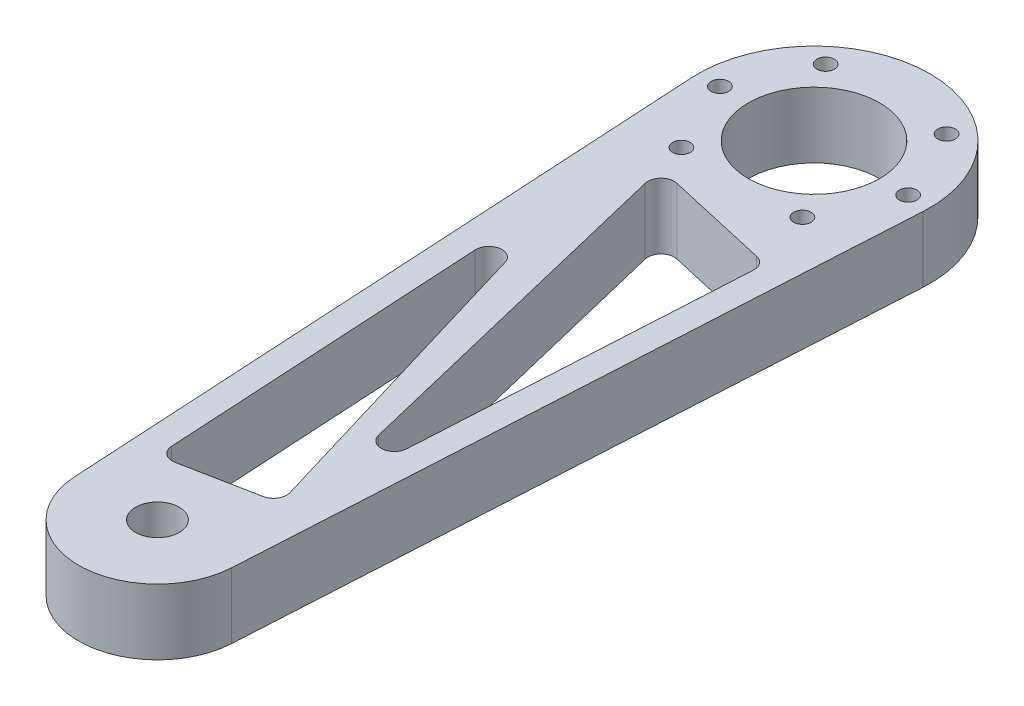
SolidWorks part; units mm, degrees
material "1060 合金"
ref_plane "前视基准面" through (0, 0, 0) normal (0, 0, 1) x (1, 0, 0)
ref_plane "上视基准面" through (0, 0, 0) normal (0, 1, 0) x (1, 0, 0)
ref_plane "右视基准面" through (0, 0, 0) normal (1, 0, 0) x (0, 0, -1)
sketch "草图1" plane through (0, 0, 0) normal (0, 1, 0) x (1, 0, 0)
  line L0 (0, 0) -> (0, 150) construction
  line L1 (-17.9711, -1.02) -> (-26.4574, 148.4983)
  line L2 (17.9711, -1.02) -> (26.4574, 148.4983)
  line L3 (-11.9807, -0.68) -> (-20.4671, 148.8383) construction
  line L4 (11.9807, -0.68) -> (20.4671, 148.8383) construction
  line L5 (-12.741, 12.7148) -> (13.0288, 17.7851) construction
  line L6 (13.0288, 17.7851) -> (18.8303, 120) construction
  line L7 (18.8303, 120) -> (-19.3219, 128.6624) construction
  line L8 (-19.3219, 128.6624) -> (-12.741, 12.7148) construction
  line L9 (13.0288, 17.7851) -> (-19.3219, 128.6624) construction
  line L10 (14.4687, 18.2052) -> (-17.882, 129.0826) construction
  line L12 (-12.741, 12.7148) -> (-18.5544, 115.1395)
  line L13 (-18.5544, 115.1395) -> (10.7129, 17.3294)
  line L14 (10.7129, 17.3294) -> (-12.741, 12.7148)
  line L15 (13.2832, 22.2683) -> (18.8303, 120)
  line L16 (-17.882, 129.0826) -> (-17.7319, 128.5683) construction
  line L17 (18.8303, 120) -> (-12, 127)
  line L18 (-12, 127) -> (13.2832, 22.2683)
  circle A0 centre (0, 150) radius 26.5 construction
  circle A1 centre (0, 0) radius 18 construction
  circle A2 centre (0, 0) radius 5
  circle A3 centre (0, 150) radius 15
  arc A4 (-17.9711, -1.02) -> (17.9711, -1.02) centre (0, 0) ccw
  arc A5 (-26.4574, 148.4983) -> (26.4574, 148.4983) centre (0, 150) cw
  arc A6 (-20.4671, 148.8383) -> (20.4671, 148.8383) centre (0, 150) cw construction
  arc A7 (-11.9807, -0.68) -> (11.9807, -0.68) centre (0, 0) ccw construction
  dimension "D2" = 53
  dimension "D3" = 36
  dimension "D4" = 10
  dimension "D5" = 30
  dimension "D1" = 150
  dimension "D9" = 30
  dimension "D10" = 23
  dimension "D11" = 12
  dimension "D6" = 6
  dimension "D7" = 1.5
extrude "凸台-拉伸1" add sketch "草图1" along normal blind 15
fillet "圆角1" radius 3 6 edges at (18.8303, 7.5, -120) (-12, 7.5, -127) (-18.5544, 7.5, -115.1395) (-12.741, 7.5, -12.7148) (13.2832, 7.5, -22.2683) (10.7129, 7.5, -17.3294)
sketch "草图2" plane through (0, 15, 0) normal (0, 1, 0) x (1, 0, 0)
  line L0 (0, 150) -> (-21.5, 150) construction
  line L1 (0, 150) -> (21.5, 150) construction
  circle A0 centre (-21.5, 150) radius 2
  circle A1 centre (21.5, 150) radius 2
  dimension "D2" = 4
  dimension "D1" = 21.5
extrude "切除-拉伸1" cut sketch "草图2" against normal through all
pattern_circular "阵列(圆周)1" [suppressed] count 3 over 360
sketch "草图3" plane through (0, 15, 0) normal (0, 1, 0) x (1, 0, 0)
  line L0 (0, 150) -> (14.25, 150) construction
  circle A0 centre (14.25, 150) radius 2
  dimension "D2" = 4
  dimension "D1" = 14.25
extrude "切除-拉伸2" [suppressed] cut sketch "草图3" against normal through all
pattern_circular "阵列(圆周)2" [suppressed] count 3 over 360
pattern_circular "阵列(圆周)3" count 2 every 50 about axis through (0, 0, -150) along (0, 1, 0) of "切除-拉伸1"
pattern_circular "阵列(圆周)4" count 2 every 50 about axis through (0, 0, -150) along (0, 1, 0) of "切除-拉伸1"
